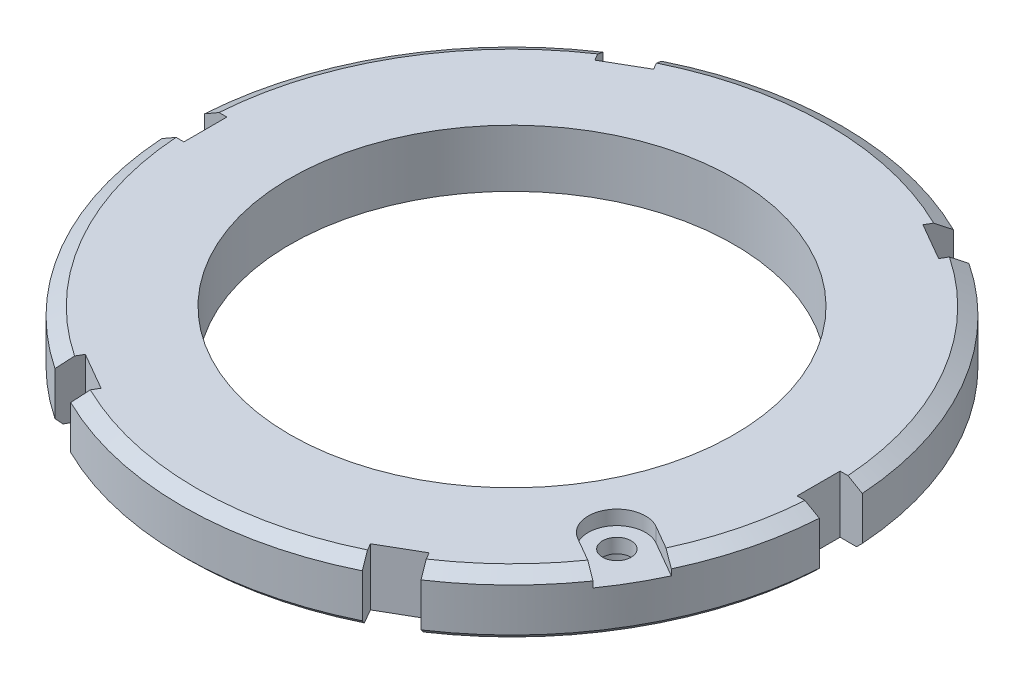
SolidWorks part; units mm, degrees
ref_plane "Спереди" through (0, 0, 0) normal (0, 0, 1) x (1, 0, 0)
ref_plane "Сверху" through (0, 0, 0) normal (0, 1, 0) x (1, 0, 0)
ref_plane "Справа" through (0, 0, 0) normal (1, 0, 0) x (0, 0, -1)
sketch "Эскиз1" plane through (0, 0, 0) normal (0, 0, 1) x (1, 0, 0)
  line L0 (0, 147.5503) -> (0, -103.5243) construction
  line L4 (115, 23.7777) -> (77.5, 23.7777)
  line L6 (77.5, 43.7777) -> (77.5, 23.7777)
  line L7 (115, 23.7777) -> (115, 40.891)
  line L8 (110, 43.7777) -> (77.5, 43.7777)
  line L9 (110, 43.7777) -> (115, 40.891)
  dimension "D1" = 230
  dimension "D2" = 20
  dimension "D3" = 155
  dimension "D4" = 30
  dimension "D5" = 220
revolve "Повернуть1" add sketch "Эскиз1" angle 360 about L0
sketch "Эскиз3" plane through (0, 43.7777, 0) normal (0, 1, 0) x (1, 0, 0)
  line L0 (0, 142.6179) -> (0, -135.2585) construction
  line L1 (-217.229, 0) -> (243.7667, 0) construction
  line L2 (0, 0) -> (139.8681, -80.7529) construction
  circle A0 centre (0, 0) radius 100 construction
  circle A1 centre (86.6025, -50) radius 5
  dimension "D2" = 200
  dimension "D3" = 10
  dimension "D1" = 30
extrude "Вырез-Вытянуть1" cut sketch "Эскиз3" against normal through all
sketch "Эскиз4" plane through (0, 23.7777, 0) normal (0, -1, 0) x (1, 0, 0)
  circle A0 centre (86.6025, 50) radius 10
  dimension "D1" = 20
extrude "Вырез-Вытянуть2" cut sketch "Эскиз4" against normal blind 10
sketch "Эскиз5" plane through (0, 43.7777, 0) normal (0, 1, 0) x (1, 0, 0)
  line L0 (91.6025, -41.3397) -> (136.1991, -67.0876)
  line L1 (81.6025, -58.6603) -> (126.7559, -84.7296)
  line L2 (0, 0) -> (139.8681, -80.7529) construction
  line L3 (126.7559, -84.7296) -> (136.1991, -67.0876)
  arc A0 (91.6025, -41.3397) -> (81.6025, -58.6603) centre (86.6025, -50) ccw
  dimension "D1" = 20
extrude "Вырез-Вытянуть3" cut sketch "Эскиз5" against normal blind 5
chamfer "Фаска2" distance 2 angle 45 1 edges at (0, 23.7777, 115)
sketch "Эскиз7" plane through (0, 0, 0) normal (0, 0, 1) x (1, 0, 0)
  line L0 (-115, 40.891) -> (-115, 2.2298) construction
  line L1 (115, 40.891) -> (-115, 40.891) construction
  line L2 (-115, 43.7777) -> (-107, 43.7777)
  line L3 (-217.229, 43.7777) -> (243.7667, 43.7777) construction
  line L4 (-107, 43.7777) -> (-107, 23.7777)
  line L5 (-113, 23.7777) -> (113, 23.7777) construction
  line L6 (-107, 23.7777) -> (-115, 23.7777)
  line L7 (-115, 23.7777) -> (-115, 43.7777)
  dimension "D1" = 8
extrude "Вырез-Вытянуть7" cut sketch "Эскиз7" against normal mid plane 15
pattern_circular "Круговой массив1" count 6 over 360 about axis through (0, 0, 0) along (0, 1, 0) of "Вырез-Вытянуть7"
